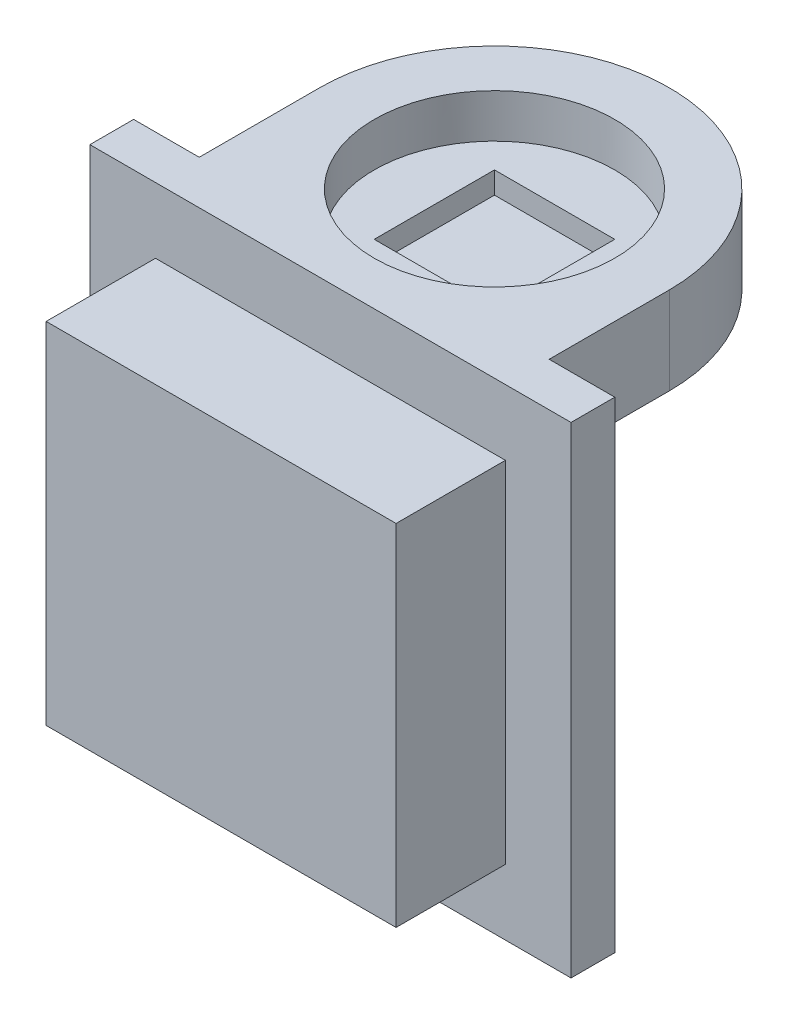
SolidWorks part; units mm, degrees
ref_plane "Front Plane" through (0, 0, 0) normal (0, 0, 1) x (1, 0, 0)
ref_plane "Top Plane" through (0, 0, 0) normal (0, 1, 0) x (1, 0, 0)
ref_plane "Right Plane" through (0, 0, 0) normal (1, 0, 0) x (0, 0, -1)
sketch "Sketch1" plane through (0, 0, 0) normal (0, 0, 1) x (1, 0, 0)
  line L1 (-8, 8) -> (8, 8)
  line L2 (-8, 8) -> (-8, -8)
  line L3 (-8, -8) -> (8, -8)
  line L4 (8, 8) -> (8, -8)
  line L5 (-8, 8) -> (8, -8) construction
  line L6 (-8, -8) -> (8, 8) construction
  line L7 (-6.25, 4.5) -> (6.25, 4.5) construction
  line L8 (-6.25, 4.5) -> (-6.25, -7) construction
  line L9 (-6.25, -7) -> (6.25, -7) construction
  line L10 (6.25, 4.5) -> (6.25, -7) construction
  point P0 (0, 0)
  point P10 (0, 4.5)
  dimension "D1" = 16
  dimension "D2" = 12.5
  dimension "D3" = 11.5
  dimension "D4" = 1
extrude "Front of switch" add sketch "Sketch1" along normal blind 1.5
sketch "Sketch2" plane through (0, 0, 0) normal (0, 0, -1) x (-1, 0, 0)
  line L0 (-7, 7) -> (-7, -7)
  line L1 (-7, -7) -> (7, -7)
  line L2 (7, -7) -> (7, 7)
  line L3 (7, 7) -> (-7, 7)
  line L4 (-8, 8) -> (-8, -8)
  line L5 (-8, -8) -> (8, -8)
  line L6 (8, -8) -> (8, 8)
  line L7 (8, 8) -> (-8, 8)
  line L8 (-8, 8) -> (-8, -8)
  line L9 (-8, -8) -> (8, -8)
  line L10 (8, -8) -> (8, 8)
  line L11 (8, 8) -> (-8, 8)
  dimension "D1" = 0
  dimension "D2" = 1
extrude "Sides of switch" add sketch "Sketch2" along normal blind 3.5
sketch "Sketch3" plane through (0, 0, -3.5) normal (0, 0, -1) x (-1, 0, 0)
  line L20 (7, 7) -> (-7, 7)
  line L21 (-7, 7) -> (-7, -7)
  line L22 (-7, -7) -> (7, -7)
  line L23 (7, -7) -> (7, 7)
  line L24 (7, 7) -> (-7, 7)
  line L25 (-7, 7) -> (-7, -7)
  line L26 (-7, -7) -> (7, -7)
  line L27 (7, -7) -> (7, 7)
  line L32 (11, 11) -> (-11, 11)
  line L33 (-11, 11) -> (-11, -11)
  line L34 (-11, -11) -> (11, -11)
  line L35 (11, -11) -> (11, 11)
  line L36 (11, 11) -> (-11, 11)
  line L37 (-11, 11) -> (-11, -11)
  line L38 (-11, -11) -> (11, -11)
  line L39 (11, -11) -> (11, 11)
  dimension "D1" = 1
  dimension "D2" = 3
extrude "Boss-Extrude3" add sketch "Sketch3" along normal blind 2
sketch "Sketch4" plane through (0, 11, 0) normal (0, 1, 0) x (1, 0, 0)
  line L0 (-11, 5.5) -> (11, 5.5) construction
  line L1 (-2.75, 13.75) -> (2.75, 13.75) construction
  line L2 (-2.75, 13.75) -> (-2.75, 8.25) construction
  line L3 (-2.75, 8.25) -> (2.75, 8.25) construction
  line L4 (2.75, 13.75) -> (2.75, 8.25) construction
  line L5 (-2.75, 13.75) -> (2.75, 8.25) construction
  line L6 (-2.75, 8.25) -> (2.75, 13.75) construction
  line L7 (-8, 5.5) -> (-8, 11)
  line L8 (-8, -1.5) -> (-8, 3.5) construction
  line L9 (8, 11) -> (8, 5.5)
  line L10 (-8, 5.5) -> (-8, 3.5)
  line L11 (-8, 3.5) -> (8, 3.5)
  line L12 (8, 3.5) -> (8, 5.5)
  circle A0 centre (0, 11) radius 5.5
  arc A1 (-8, 11) -> (8, 11) centre (0, 11) cw
  dimension "D1" = 11
  dimension "D2" = 5.5
extrude "Boss-Extrude4" add sketch "Sketch4" against normal up to surface (4 mm away) up to face at (0, 7, -2.75)
sketch "Sketch5" plane through (0, 7, 0) normal (0, -1, 0) x (1, 0, 0)
  line L1 (-2.75, -13.75) -> (2.75, -13.75)
  line L2 (-2.75, -13.75) -> (-2.75, -8.25)
  line L3 (-2.75, -8.25) -> (2.75, -8.25)
  line L4 (2.75, -13.75) -> (2.75, -8.25)
  line L5 (-2.75, -13.75) -> (2.75, -8.25) construction
  line L6 (-2.75, -8.25) -> (2.75, -13.75) construction
  circle A0 centre (0, -11) radius 5.5 construction
  circle A1 centre (0, -11) radius 5.5
  dimension "D1" = 5.5
extrude "Boss-Extrude5" add sketch "Sketch5" against normal blind 2
sketch "Sketch6" plane through (0, 7, 0) normal (0, -1, 0) x (1, 0, 0)
  line L0 (2.75, -8.25) -> (-2.75, -8.25) construction
  line L1 (-2.75, -8.25) -> (-2.75, -13.75) construction
  line L2 (-2.75, -13.75) -> (2.75, -13.75) construction
  line L3 (2.75, -13.75) -> (2.75, -8.25) construction
  line L4 (2.75, -8.25) -> (-2.75, -8.25)
  line L5 (-2.75, -8.25) -> (-2.75, -13.75)
  line L6 (-2.75, -13.75) -> (2.75, -13.75)
  line L7 (2.75, -13.75) -> (2.75, -8.25)
extrude "Boss-Extrude6" add sketch "Sketch6" against normal blind 1
